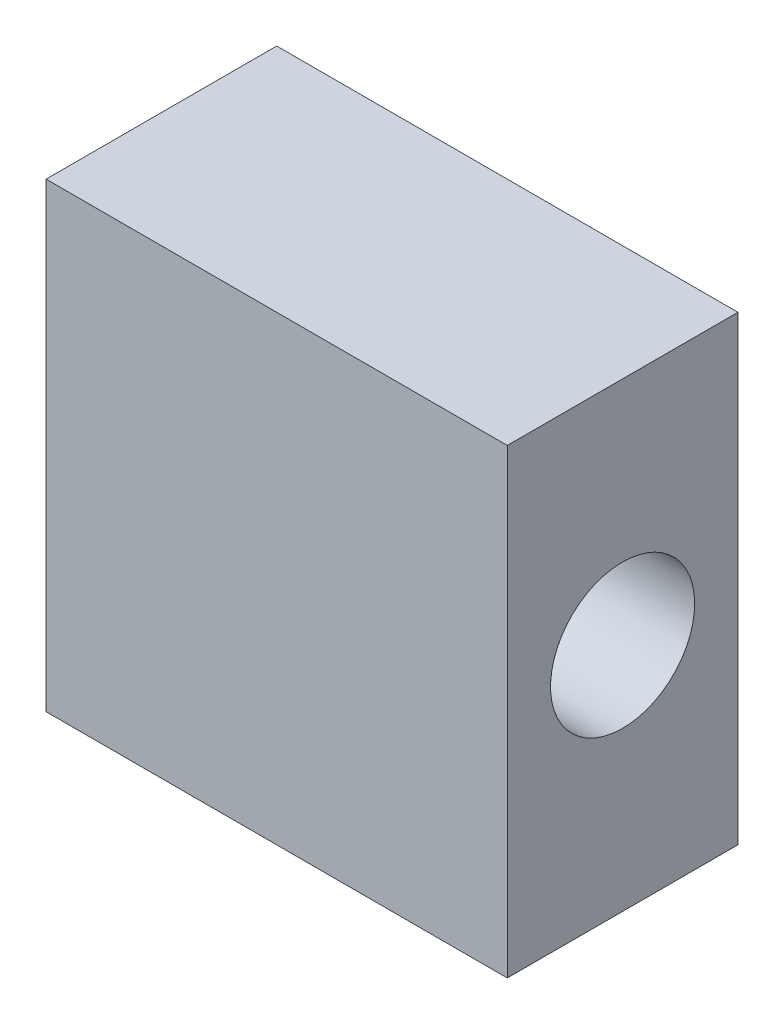
SolidWorks part; units mm, degrees
material "Brass"
ref_plane "Front Plane" through (0, 0, 0) normal (0, 0, 1) x (1, 0, 0)
ref_plane "Top Plane" through (0, 0, 0) normal (0, 1, 0) x (1, 0, 0)
ref_plane "Right Plane" through (0, 0, 0) normal (1, 0, 0) x (0, 0, -1)
sketch "Sketch1" plane through (0, 0, 0) normal (0, 0, 1) x (1, 0, 0)
  line L0 (0, 0) -> (50.8, 50.8) construction
  line L1 (0, 0) -> (50.8, 0)
  line L2 (0, 0) -> (0, 50.8)
  line L3 (0, 50.8) -> (50.8, 50.8)
  line L4 (50.8, 0) -> (50.8, 50.8)
  circle A0 centre (9.6846, 9.6846) radius 6.35 construction
  circle A1 centre (41.1154, 41.1154) radius 6.35 construction
  circle A2 centre (25.4, 25.4) radius 22.225 construction
  dimension "D2" = 44.45
  dimension "D3" = 12.7
  dimension "D1" = 50.8
extrude "Boss-Extrude1" add sketch "Sketch1" along normal blind 25.4
sketch "Sketch2" plane through (50.8, 0, 0) normal (1, 0, 0) x (0, 0, -1)
  line L0 (-25.4, 50.8) -> (0, 0) construction
  circle A0 centre (-12.7, 25.4) radius 7.9375
  dimension "D1" = 15.875
extrude "Cut-Extrude1" cut sketch "Sketch2" against normal blind 25.4
sketch "Sketch3" plane through (0, 0, 25.4) normal (0, 0, 1) x (1, 0, 0)
  line L0 (50.8, 25.4) -> (-49.1182, 25.4)
  line L1 (50.8, 0) -> (50.8, 50.8) construction
  line L2 (-49.1182, 25.4) -> (-49.1182, 47.186)
